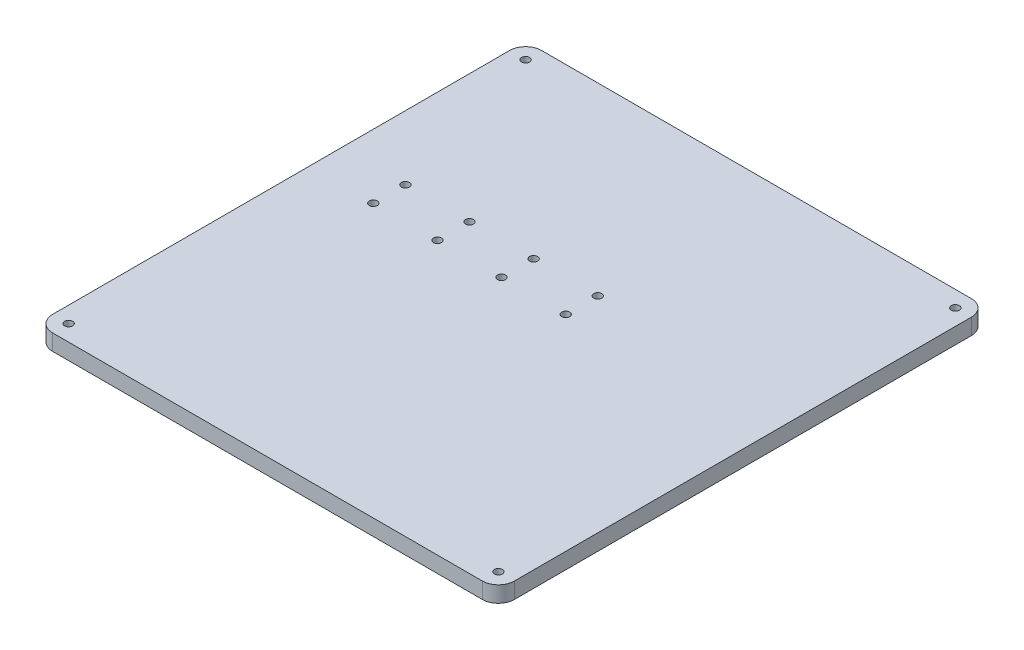
SolidWorks part; units mm, degrees
ref_plane "Front Plane" through (0, 0, 0) normal (0, 0, 1) x (1, 0, 0)
ref_plane "Top Plane" through (0, 0, 0) normal (0, 1, 0) x (1, 0, 0)
ref_plane "Right Plane" through (0, 0, 0) normal (1, 0, 0) x (0, 0, -1)
sketch "Sketch1" plane through (0, 0, 0) normal (0, 1, 0) x (1, 0, 0)
  line L0 (45.3825, 61.2661) -> (45.3825, -243.7339) construction
  line L1 (-98.6175, 61.2661) -> (189.3825, 61.2661)
  line L2 (-98.6175, 61.2661) -> (-98.6175, -243.7339)
  line L3 (-98.6175, -243.7339) -> (189.3825, -243.7339)
  line L4 (189.3825, 61.2661) -> (189.3825, -243.7339)
  line L5 (-98.6175, -91.2339) -> (189.3825, -91.2339) construction
  circle A0 centre (-58.6175, -53.7339) radius 2.5
  circle A1 centre (-18.6175, -53.7339) radius 2.5
  circle A2 centre (21.3825, -53.7339) radius 2.5
  circle A3 centre (61.3825, -53.7339) radius 2.5
  circle A4 centre (-18.6175, -73.7339) radius 2.5
  circle A5 centre (21.3825, -73.7339) radius 2.5
  circle A6 centre (61.3825, -73.7339) radius 2.5
  circle A7 centre (-58.6175, -73.7339) radius 2.5
  circle A8 centre (-88.6175, 51.2661) radius 2.5
  circle A9 centre (179.3825, 51.2661) radius 2.5
  circle A10 centre (179.3825, -233.7339) radius 2.5
  circle A11 centre (-88.6175, -233.7339) radius 2.5
  dimension "D4" = 40
  dimension "D5" = 5
  dimension "D8" = 5
  dimension "D9" = 10
  dimension "D10" = 10
  dimension "D1" = 288
  dimension "D2" = 305
  dimension "D3" = 115
  dimension "D6" = 4
  dimension "D7" = 2
extrude "Boss-Extrude1" add sketch "Sketch1" along normal blind 10
fillet "Fillet1" radius 10 4 edges at (189.3825, 5, -61.2661) (189.3825, 5, 243.7339) (-98.6175, 5, 243.7339) (-98.6175, 5, -61.2661)
